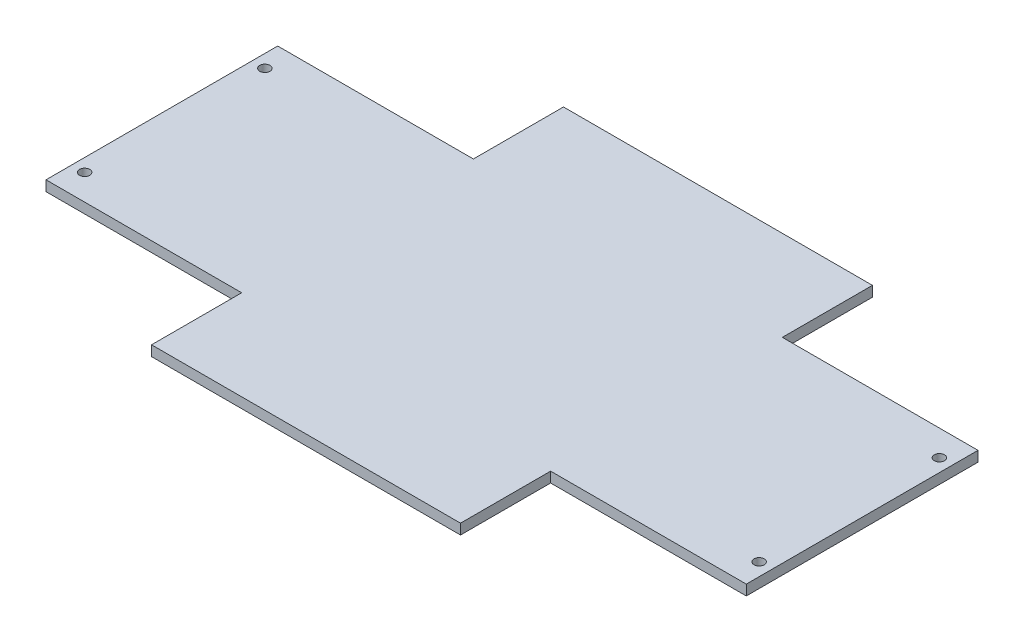
SolidWorks part; units mm, degrees
ref_plane "Front Plane" through (0, 0, 0) normal (0, 0, 1) x (1, 0, 0)
ref_plane "Top Plane" through (0, 0, 0) normal (0, 1, 0) x (1, 0, 0)
ref_plane "Right Plane" through (0, 0, 0) normal (1, 0, 0) x (0, 0, -1)
sketch "Sketch1" plane through (0, 0, 0) normal (0, 1, 0) x (1, 0, 0)
  line L0 (98, 45) -> (136, 45)
  line L1 (0, 0) -> (38, 0)
  line L2 (0, 0) -> (0, 45)
  line L3 (0, 45) -> (38, 45)
  line L4 (136, 0) -> (136, 45)
  line L5 (98, 0) -> (136, 0)
  line L6 (38, 45) -> (38, 62.5)
  line L7 (38, 62.5) -> (98, 62.5)
  line L8 (98, 45) -> (98, 62.5)
  line L10 (38, 0) -> (38, -17.5)
  line L11 (38, -17.5) -> (98, -17.5)
  line L12 (98, 0) -> (98, -17.5)
  dimension "D1" = 136
  dimension "D2" = 45
  dimension "D3" = 17.5
  dimension "D4" = 60
  dimension "D5" = 38
  dimension "D6" = 38
  dimension "D7" = 60
  dimension "D8" = 38
  dimension "D9" = 17.5
  dimension "D10" = 80
  dimension "D11" = 38
  dimension "D12" = 80
extrude "Boss-Extrude1" add sketch "Sketch1" along normal blind 2
hole_wizard "M2 Clearance Hole1" positions "Sketch3" profile "Sketch2" hole size "M2" standard "ANSI Metric"
sketch "Sketch3" plane through (0, 2, 0) normal (0, 1, 0) x (1, 0, 0)
  line L0 (38, 45) -> (0, 45) construction
  line L1 (0, 0) -> (38, 0) construction
  line L2 (0, 45) -> (0, 0) construction
  line L3 (136, 0) -> (136, 45) construction
  line L4 (136, 45) -> (98, 45) construction
  line L5 (98, 0) -> (136, 0) construction
  point P0 (2.5, 5)
  point P2 (2.5, 40)
  point P4 (133.5, 40)
  point P6 (133.5, 5)
  dimension "D1" = 35
  dimension "D2" = 5
  dimension "D3" = 5
  dimension "D4" = 2.5
  dimension "D5" = 2.5
  dimension "D6" = 2.5
  dimension "D7" = 2.5
  dimension "D8" = 35
  dimension "D9" = 5
  dimension "D10" = 5
sketch "Sketch2" plane through (2.5, 2, -5) normal (1, 0, 0) x (0, 0, 1)
  line L0 (0, 0) -> (0, 2.6009)
  line L1 (0, 2.6009) -> (1, 2)
  line L2 (1, 2) -> (1, 0)
  line L5 (1, 0) -> (0, 0)
  line L10 (0, 2.6009) -> (-1, 2) construction
  line L11 (0, -6.35) -> (0, 107.95) construction
  dimension "Hole Dia." = 2
  dimension "Hole Depth" = 2
  dimension "Drill Angle" = 118
